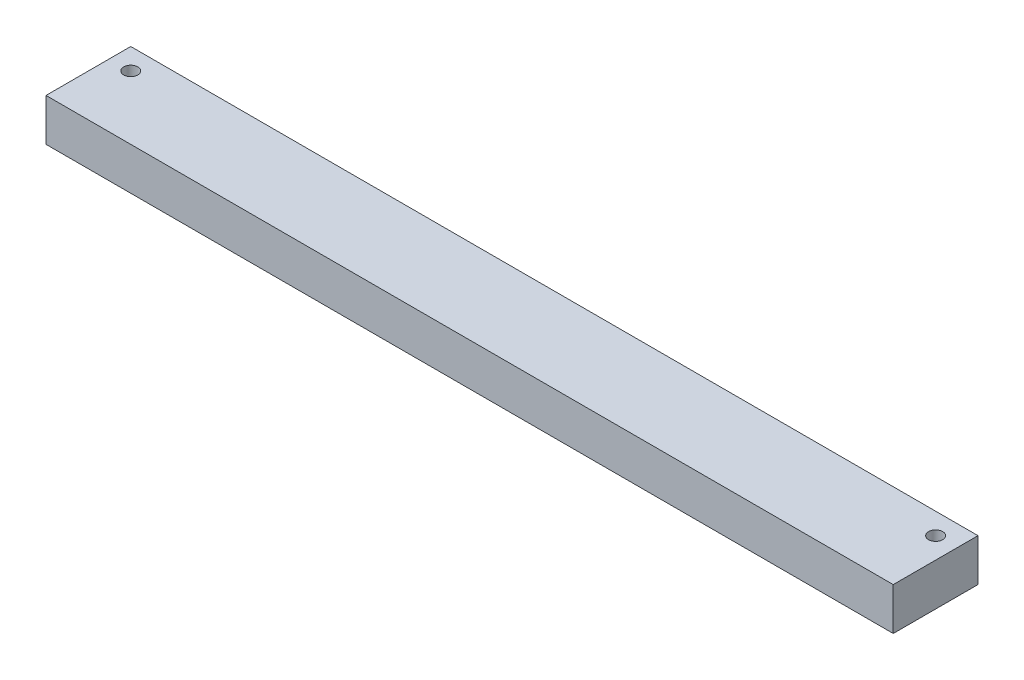
SolidWorks part; units mm, degrees
ref_plane "Front Plane" through (0, 0, 0) normal (0, 0, 1) x (1, 0, 0)
ref_plane "Top Plane" through (0, 0, 0) normal (0, 1, 0) x (1, 0, 0)
ref_plane "Right Plane" through (0, 0, 0) normal (1, 0, 0) x (0, 0, -1)
sketch "Sketch1" plane through (0, 0, 0) normal (0, 1, 0) x (1, 0, 0)
  line L0 (-29.99, 3) -> (-28.4909, 1.5009) construction
  line L1 (29.99, -3) -> (-29.99, -3)
  line L2 (29.99, -3) -> (29.99, 3)
  line L3 (29.99, 3) -> (-29.99, 3)
  line L4 (-29.99, -3) -> (-29.99, 3)
  line L5 (0, 3) -> (0, -3) construction
  circle A0 centre (-28.4909, 1.5009) radius 0.5
  circle A1 centre (28.4909, 1.5009) radius 0.5
  point P0 (0, 0)
  dimension "D3" = 1
  dimension "D1" = 59.98
  dimension "D2" = 6
  dimension "D4" = 2.12
extrude "Boss-Extrude1" add sketch "Sketch1" along normal blind 3
